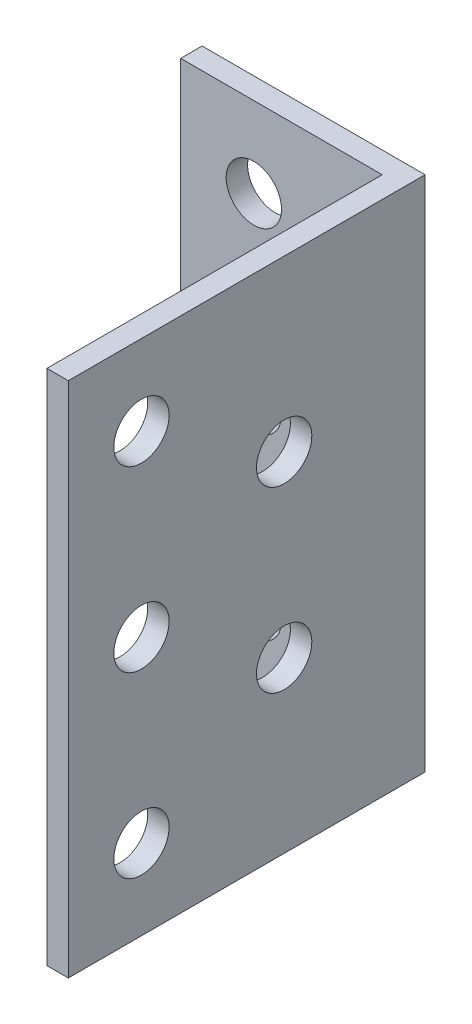
SolidWorks part; units mm, degrees
ref_plane "Front Plane" through (0, 0, 0) normal (0, 0, 1) x (1, 0, 0)
ref_plane "Top Plane" through (0, 0, 0) normal (0, 1, 0) x (1, 0, 0)
ref_plane "Right Plane" through (0, 0, 0) normal (1, 0, 0) x (0, 0, -1)
sketch "Sketch1" plane through (0, 0, 0) normal (0, 0, 1) x (1, 0, 0)
  line L1 (0, 0) -> (125, 0)
  line L2 (0, 0) -> (0, 290)
  line L3 (0, 290) -> (125, 290)
  line L4 (125, 0) -> (125, 290)
  circle A0 centre (41, 45) radius 15.5
  circle A1 centre (41, 145) radius 15.5
  circle A2 centre (41, 245) radius 15.5
  dimension "D3" = 31
  dimension "D4" = 31
  dimension "D5" = 31
  dimension "D1" = 290
  dimension "D2" = 125
  dimension "D6" = 45
  dimension "D7" = 41
  dimension "D8" = 100
  dimension "D9" = 41
  dimension "D10" = 41
  dimension "D11" = 100
extrude "Extrude1" add sketch "Sketch1" along normal blind 12
sketch "Sketch2" plane through (0, 0, 12) normal (0, 0, 1) x (1, 0, 0)
  line L0 (0, 0) -> (125, 0) construction
  line L1 (125, 290) -> (113, 290)
  line L2 (125, 290) -> (125, 0)
  line L3 (125, 0) -> (113, 0)
  line L4 (113, 290) -> (113, 0)
  dimension "D1" = 12
  dimension "D2" = 290
extrude "Extrude2" add sketch "Sketch2" along normal blind 188
sketch "Sketch3" plane through (113, 0, 0) normal (-1, 0, 0) x (0, 0, 1)
  line L0 (200, 290) -> (200, 0) construction
  line L1 (200, 0) -> (12, 0) construction
  line L2 (0, 290) -> (0, 0) construction
  line L3 (200, 290) -> (12, 290) construction
  circle A0 centre (159, 45) radius 15.5
  circle A1 centre (159, 145) radius 15.5
  circle A2 centre (159, 245) radius 15.5
  circle A3 centre (79, 95) radius 15.5
  circle A4 centre (79, 195) radius 15.5
  dimension "D1" = 41
  dimension "D3" = 31
  dimension "D4" = 31
  dimension "D5" = 31
  dimension "D10" = 31
  dimension "D11" = 31
  dimension "D2" = 45
  dimension "D6" = 100
  dimension "D7" = 100
  dimension "D8" = 41
  dimension "D9" = 41
  dimension "D12" = 79
  dimension "D13" = 79
  dimension "D14" = 95
  dimension "D15" = 100
  dimension "D16" = 95
extrude "Extrude3" cut sketch "Sketch3" against normal blind 188
